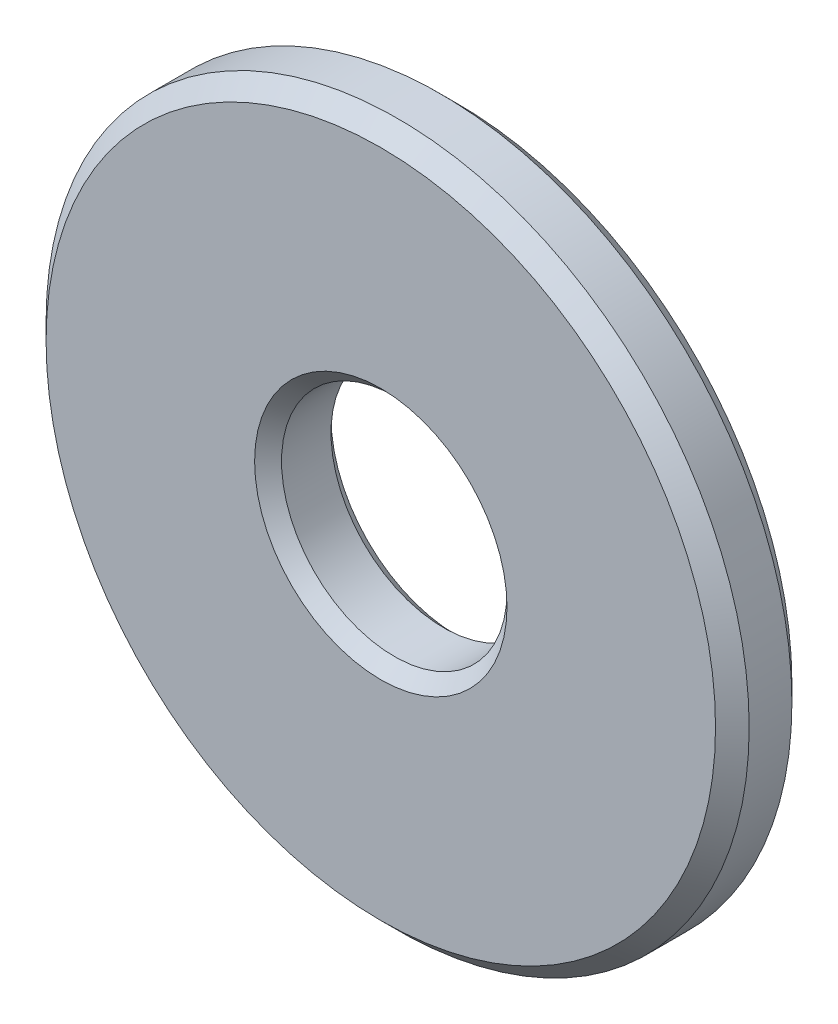
SolidWorks part; units mm, degrees
ref_plane "Front Plane" through (0, 0, 0) normal (0, 0, 1) x (1, 0, 0)
ref_plane "Top Plane" through (0, 0, 0) normal (0, 1, 0) x (1, 0, 0)
ref_plane "Right Plane" through (0, 0, 0) normal (1, 0, 0) x (0, 0, -1)
sketch "Sketch2" plane through (0, 0, 0) normal (0, 0, 1) x (1, 0, 0)
  circle A0 centre (0, 0) radius 26.534
  dimension "D1" = 53.068
extrude "Boss-Extrude1" add sketch "Sketch2" along normal blind 5.7658
chamfer "Chamfer1" distance 1.27 angle 45 2 edges at (26.534, 0, 0) (26.534, 0, 5.7658)
sketch "Sketch3" plane through (0, 0, 5.7658) normal (0, 0, 1) x (1, 0, 0)
  circle A0 centre (0, 0) radius 8.509
  dimension "D1" = 17.018
extrude "Cut-Extrude1" cut sketch "Sketch3" against normal blind 5.7658
chamfer "Chamfer2" distance 1.016 angle 45 2 edges at (8.509, 0, 0) (8.509, 0, 5.7658)
